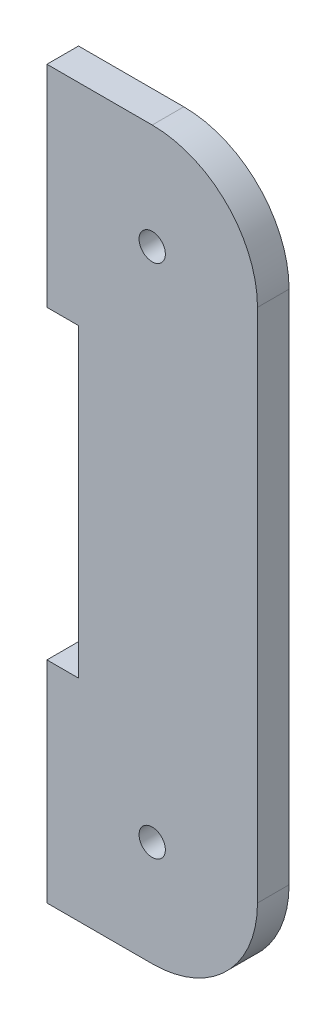
SolidWorks part; units mm, degrees
material "ABS"
ref_plane "前视基准面" through (0, 0, 0) normal (0, 0, 1) x (1, 0, 0)
ref_plane "上视基准面" through (0, 0, 0) normal (0, 1, 0) x (1, 0, 0)
ref_plane "右视基准面" through (0, 0, 0) normal (1, 0, 0) x (0, 0, -1)
sketch "草图1" plane through (0, 0, 0) normal (0, 0, 1) x (1, 0, 0)
  line L1 (-10.2041, 54.051) -> (9.7959, 54.051)
  line L2 (-10.2041, 54.051) -> (-10.2041, -14.949)
  line L3 (-10.2041, -14.949) -> (9.7959, -14.949)
  line L4 (9.7959, 54.051) -> (9.7959, -14.949)
  dimension "D1" = 20
  dimension "D2" = 69
extrude "凸台-拉伸1" add sketch "草图1" along normal blind 3
sketch "草图2" plane through (0, 0, 0) normal (0, 0, 1) x (1, 0, 0)
  line L0 (-10.2041, 54.051) -> (-10.2041, -14.949) construction
  line L1 (-10.2041, 34.051) -> (-7.2041, 34.051)
  line L2 (-10.2041, 34.051) -> (-10.2041, 5.051)
  line L3 (-10.2041, 5.051) -> (-7.2041, 5.051)
  line L4 (-7.2041, 34.051) -> (-7.2041, 5.051)
  line L5 (9.7959, 54.051) -> (-10.2041, 54.051) construction
  dimension "D1" = 20
  dimension "D2" = 29
  dimension "D3" = 3
extrude "切除-拉伸1" cut sketch "草图2" along normal blind 3
sketch "草图4" plane through (0, 0, 0) normal (0, 0, -1) x (-1, 0, 0)
  line L0 (0.2041, 54.051) -> (0.2041, -14.949) construction
  line L1 (-9.7959, 54.051) -> (10.2041, 54.051) construction
  line L2 (10.2041, -14.949) -> (-9.7959, -14.949) construction
  point P6 (0.2041, 44.051)
  point P7 (0.2041, -4.949)
  dimension "D1" = 10
  dimension "D2" = 10
hole_wizard "M3 螺纹孔的螺纹孔钻头1" positions "草图9" profile "草图10" hole size "M3" standard "AS" end condition through all
sketch "草图9" plane through (0, 0, 0) normal (0, 0, -1) x (-1, 0, 0)
  point P0 (0.2041, 44.051)
  point P3 (0.2041, -4.949)
sketch "草图10" plane through (-0.2041, 44.051, 0) normal (1, 0, 0) x (0, 1, 0)
  line L0 (0, 0) -> (0, 3)
  line L1 (0, 3) -> (1.25, 3)
  line L2 (1.25, 3) -> (1.25, 0)
  line L5 (1.25, 0) -> (0, 0)
  line L11 (0, -6.35) -> (0, 107.95) construction
  dimension "通孔孔直径" = 2.5
  dimension "通孔孔深度" = 3
fillet "圆角1" radius 10 2 edges at (9.7959, -14.949, 1.5) (9.7959, 54.051, 1.5)
